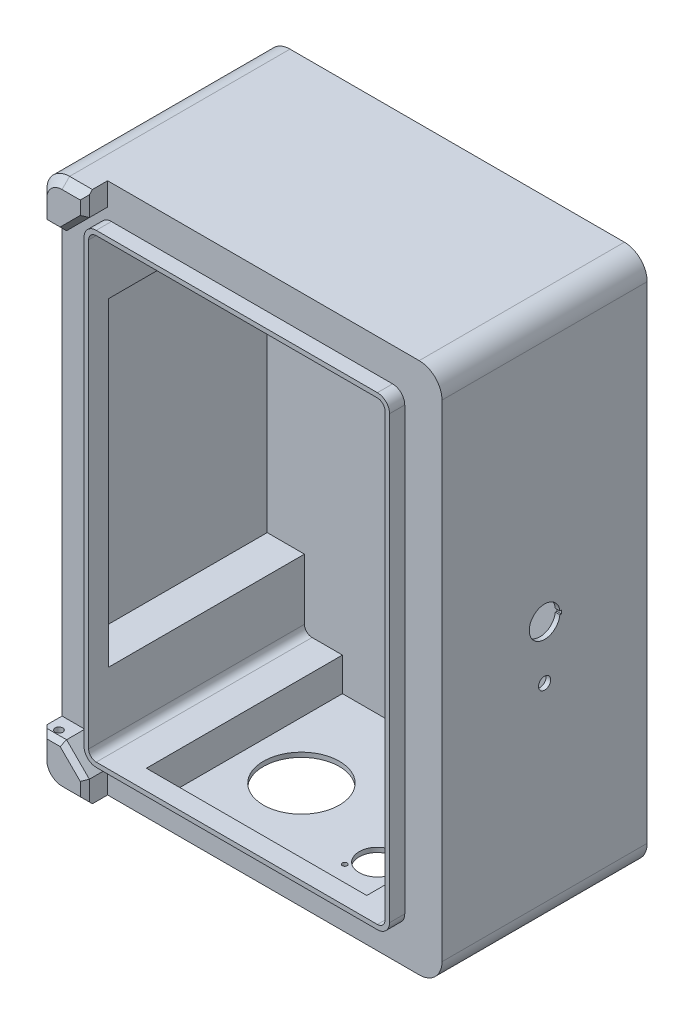
SolidWorks part; units mm, degrees
ref_plane "Front Plane" through (0, 0, 0) normal (0, 0, 1) x (1, 0, 0)
ref_plane "Top Plane" through (0, 0, 0) normal (0, 1, 0) x (1, 0, 0)
ref_plane "Right Plane" through (0, 0, 0) normal (1, 0, 0) x (0, 0, -1)
sketch "Sketch1" plane through (0, 0, 0) normal (0, 0, 1) x (1, 0, 0)
  line L1 (15, 0) -> (235, 0)
  line L2 (0, 15) -> (0, 335)
  line L3 (15, 350) -> (235, 350)
  line L4 (250, 15) -> (250, 335)
  arc A0 (0, 15) -> (15, 0) centre (15, 15) ccw
  arc A1 (235, 0) -> (250, 15) centre (235, 15) ccw
  arc A2 (250, 335) -> (235, 350) centre (235, 335) ccw
  arc A3 (15, 350) -> (0, 335) centre (15, 335) ccw
  point P7 (0, 0)
  point P10 (250, 0)
  dimension "D3" = 15
  dimension "D1" = 350
  dimension "D2" = 250
extrude "Boss-Extrude1" add sketch "Sketch1" along normal blind 3
sketch "Sketch2" plane through (0, 0, 3) normal (0, 0, 1) x (1, 0, 0)
  line L1 (32.5, 25) -> (217.5, 25)
  line L2 (27.5, 30) -> (27.5, 320)
  line L3 (32.5, 325) -> (217.5, 325)
  line L4 (15, 0) -> (235, 0)
  line L5 (250, 15) -> (250, 335)
  line L6 (235, 350) -> (15, 350)
  line L7 (0, 335) -> (0, 15)
  line L8 (15, 0) -> (235, 0)
  line L9 (250, 15) -> (250, 335)
  line L10 (235, 350) -> (15, 350)
  line L11 (0, 335) -> (0, 15)
  line L12 (222.5, 30) -> (222.5, 320)
  arc A0 (27.5, 30) -> (32.5, 25) centre (32.5, 30) ccw
  arc A1 (217.5, 25) -> (222.5, 30) centre (217.5, 30) ccw
  arc A2 (222.5, 320) -> (217.5, 325) centre (217.5, 320) ccw
  arc A3 (32.5, 325) -> (27.5, 320) centre (32.5, 320) ccw
  arc A4 (0, 15) -> (15, 0) centre (15, 15) ccw
  arc A5 (235, 0) -> (250, 15) centre (235, 15) ccw
  arc A6 (250, 335) -> (235, 350) centre (235, 335) ccw
  arc A7 (15, 350) -> (0, 335) centre (15, 335) ccw
  arc A8 (0, 15) -> (15, 0) centre (15, 15) ccw
  arc A9 (235, 0) -> (250, 15) centre (235, 15) ccw
  arc A10 (250, 335) -> (235, 350) centre (235, 335) ccw
  arc A11 (15, 350) -> (0, 335) centre (15, 335) ccw
  arc M17 (0, 15) -> (15, 0) centre (15, 15) ccw
  line M18 (15, 0) -> (235, 0)
  arc M19 (235, 0) -> (250, 15) centre (235, 15) ccw
  line M20 (250, 15) -> (250, 335)
  arc M21 (250, 335) -> (235, 350) centre (235, 335) ccw
  line M22 (235, 350) -> (15, 350)
  arc M23 (15, 350) -> (0, 335) centre (15, 335) ccw
  line M24 (0, 335) -> (0, 15)
  dimension "D6" = 5
  dimension "D2" = 25
  dimension "D3" = 27.5
  dimension "D4" = 27.5
  dimension "D5" = 25
  dimension "D1" = 0
extrude "Boss-Extrude2" add sketch "Sketch2" along normal blind 132 contours A3 L3 A2 L12 A1 L1 A0 L2 M24 M17 M18 M19 M20 M21 M22 M23
sketch "Sketch3" plane through (27.5, 0, 0) normal (1, 0, 0) x (0, 0, -1)
  line L0 (-3, 30) -> (-3, 320) construction
  line L1 (-3, 280) -> (-132, 280)
  line L2 (-3, 280) -> (-3, 70)
  line L3 (-3, 70) -> (-132, 70)
  line L4 (-132, 280) -> (-132, 70)
  line L5 (-135, 30) -> (-135, 320) construction
  line L6 (-135, 30) -> (-3, 30) construction
  line L7 (-135, 320) -> (-3, 320) construction
  dimension "D1" = 3
  dimension "D2" = 40
  dimension "D3" = 40
extrude "Cut-Extrude1" cut sketch "Sketch3" against normal offset from surface 3 and the other way offset from surface (219.5 mm away) 3 up to face at (0, 175, 67.5) other way up to face at (250, 175, 67.5)
sketch "Sketch5" plane through (0, 25, 0) normal (0, 1, 0) x (1, 0, 0)
  line L0 (32.5, -3) -> (217.5, -3) construction
  line L1 (197.5, -3) -> (52.5, -3)
  line L2 (197.5, -3) -> (197.5, -132)
  line L3 (197.5, -132) -> (52.5, -132)
  line L4 (52.5, -3) -> (52.5, -132)
  line L5 (32.5, -135) -> (217.5, -135) construction
  line L6 (217.5, -135) -> (217.5, -3) construction
  line L7 (32.5, -135) -> (32.5, -3) construction
  dimension "D1" = 3
  dimension "D2" = 20
  dimension "D3" = 20
extrude "Cut-Extrude2" cut sketch "Sketch5" against normal offset from surface 3 and the other way offset from surface (322 mm away) 3 up to face at (125, 0, 67.5) other way up to face at (125, 350, 67.5)
sketch "Sketch8" plane through (0, 0, 135) normal (0, 0, 1) x (1, 0, 0)
  line L20 (32.5, 25) -> (217.5, 25) construction
  line L21 (27.5, 30) -> (27.5, 320) construction
  line L22 (32.5, 325) -> (217.5, 325) construction
  line L23 (222.5, 30) -> (222.5, 320) construction
  line L24 (225.5, 30) -> (225.5, 320)
  line L25 (32.5, 22) -> (217.5, 22)
  line L26 (24.5, 320) -> (24.5, 30)
  line L27 (217.5, 328) -> (32.5, 328)
  line L28 (225.5, 30) -> (225.5, 320)
  line L29 (32.5, 22) -> (217.5, 22)
  line L30 (24.5, 320) -> (24.5, 30)
  line L31 (217.5, 328) -> (32.5, 328)
  line L32 (32.5, 25) -> (217.5, 25)
  line L33 (27.5, 30) -> (27.5, 320)
  line L34 (32.5, 325) -> (217.5, 325)
  line L35 (222.5, 30) -> (222.5, 320)
  arc A16 (217.5, 25) -> (222.5, 30) centre (217.5, 30) ccw construction
  arc A17 (27.5, 30) -> (32.5, 25) centre (32.5, 30) ccw construction
  arc A18 (32.5, 325) -> (27.5, 320) centre (32.5, 320) ccw construction
  arc A19 (222.5, 320) -> (217.5, 325) centre (217.5, 320) ccw construction
  arc A20 (225.5, 320) -> (217.5, 328) centre (217.5, 320) ccw
  arc A21 (217.5, 22) -> (225.5, 30) centre (217.5, 30) ccw
  arc A22 (24.5, 30) -> (32.5, 22) centre (32.5, 30) ccw
  arc A23 (32.5, 328) -> (24.5, 320) centre (32.5, 320) ccw
  arc A24 (225.5, 320) -> (217.5, 328) centre (217.5, 320) ccw
  arc A25 (217.5, 22) -> (225.5, 30) centre (217.5, 30) ccw
  arc A26 (24.5, 30) -> (32.5, 22) centre (32.5, 30) ccw
  arc A27 (32.5, 328) -> (24.5, 320) centre (32.5, 320) ccw
  arc A28 (217.5, 25) -> (222.5, 30) centre (217.5, 30) ccw
  arc A29 (27.5, 30) -> (32.5, 25) centre (32.5, 30) ccw
  arc A30 (32.5, 325) -> (27.5, 320) centre (32.5, 320) ccw
  arc A31 (222.5, 320) -> (217.5, 325) centre (217.5, 320) ccw
  dimension "D1" = 3
extrude "Boss-Extrude3" add sketch "Sketch8" along normal blind 10
sketch "Sketch9" plane through (0, 0, 135) normal (0, 0, 1) x (1, 0, 0)
  line L0 (15, 0) -> (235, 0) construction
  line L1 (0, 335) -> (0, 15) construction
  line L2 (235, 350) -> (15, 350) construction
  line L3 (15, 0) -> (235, 0)
  line L4 (0, 335) -> (0, 15)
  line L5 (235, 350) -> (15, 350)
  line L6 (0, 320) -> (15, 320)
  line L7 (15, 320) -> (30, 335)
  line L8 (30, 335) -> (30, 350)
  line L9 (0, 30) -> (15, 30)
  line L10 (15, 30) -> (30, 15)
  line L11 (30, 15) -> (30, 0)
  arc A0 (0, 15) -> (15, 0) centre (15, 15) ccw construction
  arc A1 (15, 350) -> (0, 335) centre (15, 335) ccw construction
  arc A2 (0, 15) -> (15, 0) centre (15, 15) ccw
  arc A3 (15, 350) -> (0, 335) centre (15, 335) ccw
  line M9 (0, 335) -> (0, 15)
  arc M10 (0, 15) -> (15, 0) centre (15, 15) ccw
  line M11 (15, 0) -> (235, 0)
  arc M16 (15, 350) -> (0, 335) centre (15, 335) ccw
  dimension "D1" = 45
  dimension "D2" = 15
  dimension "D3" = 15
  dimension "D4" = 45
  dimension "D5" = 15
  dimension "D6" = 15
  dimension "D7" = 30
  dimension "D8" = 30
extrude "Boss-Extrude4" add sketch "Sketch9" along normal blind 15 contours L11 L10 L9 M9 M10 M11 | L7 L8 L5 L6 M16 M9
chamfer "Chamfer1" distance 5 angle 45 6 edges at (22.5, 0, 150) (4.3934, 4.3934, 150) (0, 22.5, 150) (22.5, 350, 150) (4.3934, 345.6066, 150) (0, 327.5, 150)
chamfer "Chamfer2" distance 3 angle 45 6 edges at (30, 10, 150) (22.5, 22.5, 150) (10, 30, 150) (30, 340, 150) (22.5, 327.5, 150) (10, 320, 150)
sketch "Sketch10" plane through (0, 30, 0) normal (0, 1, 0) x (1, 0, 0)
  line L0 (0, -145) -> (0, -135) construction
  line L1 (13.7574, -150) -> (5, -150) construction
  circle A0 centre (7, -144) radius 2.5
  dimension "D3" = 5
  dimension "D1" = 7
  dimension "D2" = 6
extrude "Cut-Extrude3" cut sketch "Sketch10" against normal blind 5 and the other way offset from surface (295 mm away) 5 other way up to face at (6.4, 320, 141.8)
sketch "Sketch11" plane through (0, 3, 0) normal (0, 1, 0) x (1, 0, 0)
  line L0 (15, -67.5) -> (235, -67.5) construction
  line L1 (235, -135) -> (235, 0) construction
  line L3 (125, -3) -> (125, -132) construction
  line L4 (52.5, -3) -> (197.5, -3) construction
  line L5 (197.5, -132) -> (52.5, -132) construction
  line L8 (169.5, -75.5) -> (150.5, -99.5) construction
  circle A0 centre (160, -87.5) radius 12
  circle A1 centre (145, -47.5) radius 7.6
  circle A2 centre (175, -47.5) radius 7.6
  circle A3 centre (90, -67.5) radius 25
  circle A4 centre (150.5, -99.5) radius 1.6
  circle A5 centre (169.5, -75.5) radius 1.6
  dimension "D1" = 24
  dimension "D3" = 15.2
  dimension "D5" = 15.2
  dimension "D2" = 50
  dimension "D13" = 3.2
  dimension "D14" = 3.2
  dimension "D4" = 35
  dimension "D6" = 35
  dimension "D7" = 20
  dimension "D8" = 50
  dimension "D9" = 20
  dimension "D10" = 20
  dimension "D11" = 20
  dimension "D12" = 19
  dimension "D15" = 24
extrude "Cut-Extrude4" cut sketch "Sketch11" against normal blind 10
sketch "Sketch13" plane through (247, 0, 0) normal (-1, 0, 0) x (0, 0, 1)
  line L0 (67.5, 335) -> (67.5, 15) construction
  line L3 (135, 335) -> (0, 335) construction
  line L4 (135, 15) -> (0, 15) construction
  line L5 (0, 175) -> (135, 175) construction
  line L6 (0, 15) -> (0, 335) construction
  line L7 (135, 15) -> (135, 335) construction
  line L8 (57.4601, 173.9) -> (56.5, 173.9)
  line L16 (56.5, 173.9) -> (56.5, 176.1)
  line L17 (77.5499, 173.995) -> (56.5, 176.1) construction
  line L18 (77.5499, 176.005) -> (56.5, 173.9) construction
  line L19 (57.4601, 176.1) -> (56.5, 176.1)
  circle A1 centre (67.5, 140) radius 4
  arc A3 (57.4601, 173.9) -> (57.4601, 176.1) centre (67.5, 175) ccw
  dimension "D1" = 20.2
  dimension "D2" = 8
  dimension "D3" = 2.2
  dimension "D4" = 11
extrude "Cut-Extrude6" cut sketch "Sketch13" against normal blind 10 contours A3 L19 L16 L8 | A1
